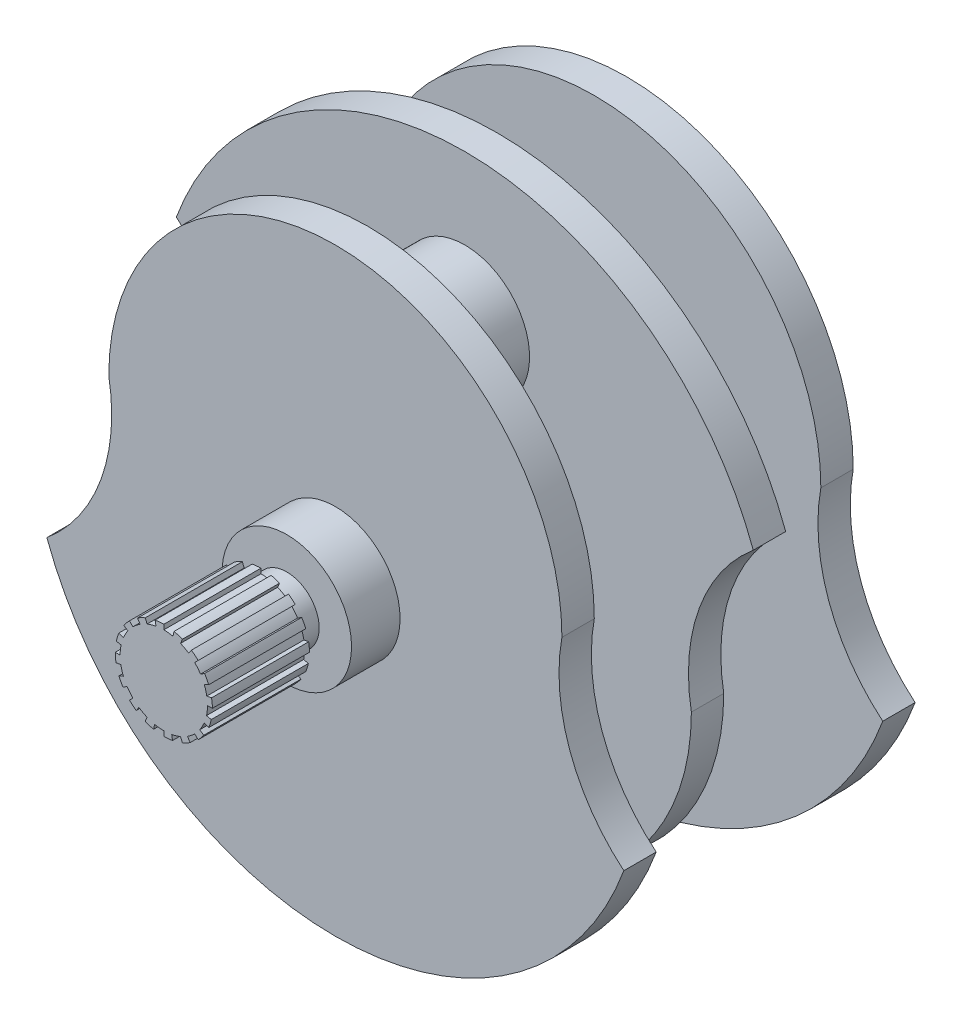
SolidWorks part; units mm, degrees
material "AISI 4340 Steel, annealed"
ref_plane "Front Plane" through (0, 0, 0) normal (0, 0, 1) x (1, 0, 0)
ref_plane "Top Plane" through (0, 0, 0) normal (0, 1, 0) x (1, 0, 0)
ref_plane "Right Plane" through (0, 0, 0) normal (1, 0, 0) x (0, 0, -1)
sketch "Sketch1" plane through (0, 0, 0) normal (0, 0, 1) x (1, 0, 0)
  circle A0 centre (0, 0) radius 20
  dimension "D1" = 20
extrude "Boss-Extrude1" add sketch "Sketch1" along normal blind 15
sketch "Sketch2" plane through (0, 0, 15) normal (0, 0, 1) x (1, 0, 0)
  circle A0 centre (0, 0) radius 10
  dimension "D1" = 10
extrude "Boss-Extrude2" add sketch "Sketch2" along normal blind 8
sketch "Sketch3" plane through (0, 0, 23) normal (0, 0, 1) x (1, 0, 0)
  circle A0 centre (0, 0) radius 15
  dimension "D1" = 15
extrude "Boss-Extrude3" add sketch "Sketch3" along normal blind 30
sketch "Sketch5" plane through (0, 0, 53) normal (0, 0, 1) x (1, 0, 0)
  line L0 (0, 15) -> (0, 13.5)
  line L1 (2.8421, 13.1974) -> (3.1579, 14.6638)
  circle A0 centre (0, 0) radius 15 construction
  arc A1 (0, 13.5) -> (2.8421, 13.1974) centre (0, 0) cw
  arc A2 (3.1579, 14.6638) -> (0, 15) centre (0, 0) ccw
  circle A3 centre (0, 0) radius 15
  point P8 (0, 14.25)
  circle M6 centre (0, 0) radius 15
  dimension "D1" = 13.5
  dimension "D2" = 3
extrude "Cut-Extrude1" cut sketch "Sketch5" against normal up to next contours L0 A1 L1 M6
pattern_circular "CirPattern1" count 16 over 360 about axis through (0, 0, 0) along (0, 0, 1) of "Cut-Extrude1"
sketch "Sketch8" plane through (0, 0, 0) normal (0, 0, -1) x (-1, 0, 0)
  arc A0 (70, 20) -> (-70, 20) centre (0, 20) ccw
  arc A5 (-89.1301, -32.876) -> (89.1301, -32.876) centre (0, 0) ccw
  arc A6 (-70, 20) -> (-89.1301, -32.876) centre (-125, 10) cw
  arc A7 (70, 20) -> (89.1301, -32.876) centre (125, 10) ccw
  point P9 (-69.8019, 25.2622)
  point P10 (0, 0)
  point P11 (-89.1301, -32.876)
  dimension "D1" = 70
  dimension "D2" = 95
  dimension "D3" = 20
  dimension "D5" = 10
  dimension "D6" = 125
extrude "Boss-Extrude5" add sketch "Sketch8" along normal blind 10
sketch "Sketch9" plane through (0, 0, -10) normal (0, 0, -1) x (-1, 0, 0)
  circle A0 centre (0, 50) radius 20
  dimension "D2" = 20
  dimension "D1" = 50
extrude "Boss-Extrude6" add sketch "Sketch9" along normal blind 30
sketch "Sketch10" plane through (0, 0, -40) normal (0, 0, -1) x (-1, 0, 0)
  arc A0 (-70, -20) -> (70, -20) centre (0, -20) ccw
  arc A1 (-70, -20) -> (-89.1301, 32.876) centre (-125, -10) ccw
  arc A2 (70, -20) -> (89.1301, 32.876) centre (125, -10) cw
  arc A3 (-89.1301, 32.876) -> (89.1301, 32.876) centre (0, 0) cw
  dimension "D1" = 70
  dimension "D3" = 95
  dimension "D2" = 20
  dimension "D4" = 125
  dimension "D5" = 10
extrude "Boss-Extrude7" add sketch "Sketch10" along normal blind 10
ref_plane "Plane3" through (0, 0, -80) normal (0, 0, -1) x (-1, 0, 0)
sketch "Sketch12" plane through (0, 0, -80) normal (0, 0, -1) x (-1, 0, 0)
  arc A4 (70, 20) -> (-70, 20) centre (0, 20) ccw
  arc A5 (-89.1301, -32.876) -> (-70, 20) centre (-125, 10) ccw
  arc A6 (-89.1301, -32.876) -> (89.1301, -32.876) centre (0, 0) ccw
  arc A7 (70, 20) -> (89.1301, -32.876) centre (125, 10) ccw
  arc A8 (70, 20) -> (-70, 20) centre (0, 20) ccw
  arc A9 (-89.1301, -32.876) -> (-70, 20) centre (-125, 10) ccw
  arc A10 (-89.1301, -32.876) -> (89.1301, -32.876) centre (0, 0) ccw
  arc A11 (70, 20) -> (89.1301, -32.876) centre (125, 10) ccw
  point P0 (0, 0)
  dimension "D1" = 0
extrude "Boss-Extrude8" add sketch "Sketch12" along normal blind 10 separate body
sketch "Sketch14" plane through (0, 0, -50) normal (0, 0, -1) x (-1, 0, 0)
  circle A0 centre (0, -50) radius 20
  dimension "D2" = 20
  dimension "D1" = 50
extrude "Boss-Extrude9" add sketch "Sketch14" along normal up to next
sketch "Sketch15" plane through (0, 0, -90) normal (0, 0, -1) x (-1, 0, 0)
  circle A1 centre (0, 0) radius 20
  circle A2 centre (0, 0) radius 20
  dimension "D1" = 0
extrude "Boss-Extrude10" add sketch "Sketch15" along normal blind 15
sketch "Sketch16" plane through (0, 0, -105) normal (0, 0, -1) x (-1, 0, 0)
  circle A1 centre (0, 0) radius 10
  circle A2 centre (0, 0) radius 10
  dimension "D1" = 0
extrude "Boss-Extrude11" add sketch "Sketch16" along normal blind 8
